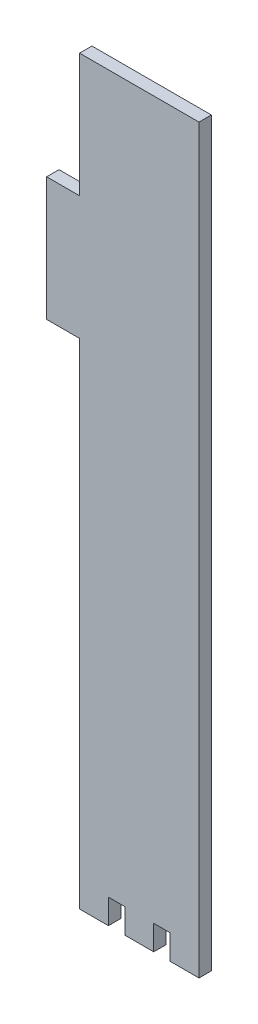
SolidWorks part; units mm, degrees
ref_plane "Plan de face" through (0, 0, 0) normal (0, 0, 1) x (1, 0, 0)
ref_plane "Plan de dessus" through (0, 0, 0) normal (0, 1, 0) x (1, 0, 0)
ref_plane "Plan de droite" through (0, 0, 0) normal (1, 0, 0) x (0, 0, -1)
sketch "Esquisse1" plane through (0, 0, 0) normal (0, 0, 1) x (1, 0, 0)
  line L1 (0, 0) -> (-29, 0)
  line L2 (0, 0) -> (0, 180)
  line L3 (0, 180) -> (-29, 180)
  line L4 (-29, 0) -> (-29, 180)
  line L5 (-29, 0) -> (-22, 0)
  line L6 (-29, 0) -> (-29, 6)
  line L7 (-29, 6) -> (-22, 6)
  line L8 (-22, 0) -> (-22, 6)
  line L9 (0, 0) -> (-7, 0)
  line L10 (0, 0) -> (0, 6)
  line L11 (0, 6) -> (-7, 6)
  line L12 (-7, 0) -> (-7, 6)
  line L13 (-10.1626, 0) -> (-18.1626, 0)
  line L14 (-29, 150) -> (-37, 150)
  line L15 (-11, 6) -> (-18, 6)
  line L16 (-29, 150) -> (-29, 120)
  line L17 (-22, 6) -> (-18, 6)
  line L18 (-22, 6) -> (-22, 0)
  line L19 (-22, 0) -> (-18.1626, 0)
  line L20 (-29, 120) -> (-37, 120)
  line L21 (-11, 6) -> (-7, 6)
  line L22 (-37, 150) -> (-37, 120)
  line L23 (-10.1626, 0) -> (-7, 0)
  line L24 (-7, 6) -> (-7, 0)
  line L25 (-18, 6) -> (-11, 6)
  line L26 (-18, 6) -> (-18, 0)
  line L27 (-18, 0) -> (-11, 0)
  line L29 (-18, 6) -> (-11, 6)
  line L30 (-18, 6) -> (-18, 0)
  line L31 (-18, 0) -> (-11, 0)
  line L32 (-11, 6) -> (-11, 0)
  dimension "D1" = 29
  dimension "D2" = 180
  dimension "D3" = 6
  dimension "D4" = 7
  dimension "D5" = 7
  dimension "D6" = 4
  dimension "D7" = 30
  dimension "D8" = 30
  dimension "D9" = 8
  dimension "D10" = 4
extrude "Boss.-Extru.1" add sketch "Esquisse1" along normal blind 3 contours L14 L22 L20 L4 | L15 L21 L11 L2 L3 L4 L7 L17 | L1 L8 L7 L4 | L32 L15 L17 L26 L1 L13 | L12 L1 L2 L11
